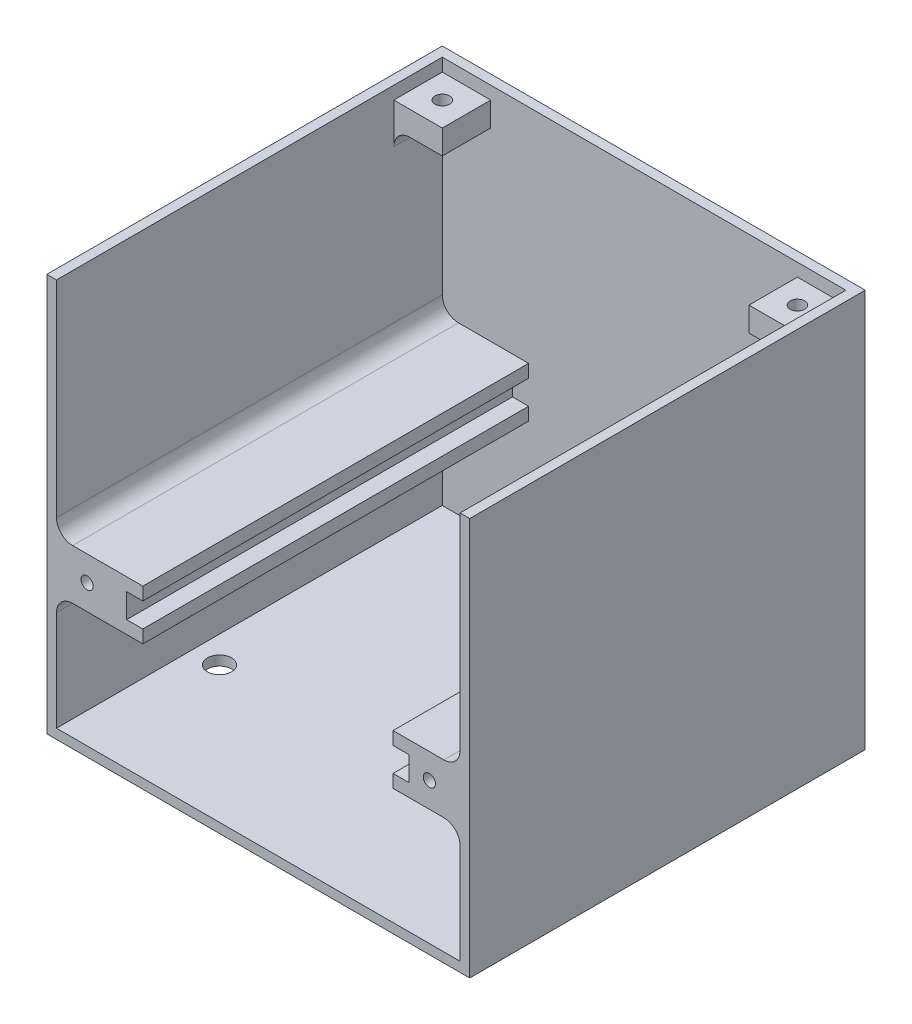
SolidWorks part; units mm, degrees
ref_plane "Front Plane" through (0, 0, 0) normal (0, 0, 1) x (1, 0, 0)
ref_plane "Top Plane" through (0, 0, 0) normal (0, 1, 0) x (1, 0, 0)
ref_plane "Right Plane" through (0, 0, 0) normal (1, 0, 0) x (0, 0, -1)
sketch "Sketch1" plane through (0, 0, 0) normal (0, 0, 1) x (1, 0, 0)
  line L0 (25, 1.2) -> (25, 49.3) construction
  line L1 (-26.2, 0) -> (26.2, 0)
  line L2 (-26.2, 0) -> (-26.2, 49.3)
  line L3 (-26.2, 49.3) -> (-25, 49.3) construction
  line L4 (26.2, 0) -> (26.2, 49.3)
  line L5 (-25, 1.2) -> (25, 1.2) construction
  line L6 (-25, 1.2) -> (-25, 49.3) construction
  line L7 (25, 49.3) -> (26.2, 49.3) construction
  line L8 (26.2, 49.3) -> (-26.2, 49.3)
  point P4 (0, 0)
  dimension "D1" = 52.4
  dimension "D2" = 49.3
  dimension "D3" = 1.2
extrude "Boss-Extrude1" add sketch "Sketch1" along normal blind 49
sketch "Sketch2" plane through (0, 0, 49) normal (0, 0, 1) x (1, 0, 0)
  line L0 (25, 1.2) -> (25, 49.3) construction
  line L1 (-25, 1.2) -> (25, 1.2) construction
  line L2 (-25, 1.2) -> (-25, 49.3) construction
  line L3 (26.2, 49.3) -> (-26.2, 49.3) construction
  line L4 (25, 1.2) -> (25, 15.6)
  line L5 (-25, 1.2) -> (25, 1.2)
  line L6 (-25, 1.2) -> (-25, 15.6)
  line L7 (25, 49.3) -> (-25, 49.3)
  line L8 (-25, 21.8) -> (-25, 49.3)
  line L9 (-16.3, 17.2) -> (-16.3, 20.2)
  line L10 (-25, 15.6) -> (-14.3, 15.6)
  line L11 (-16.3, 17.2) -> (-14.3, 17.2)
  line L12 (-16.3, 20.2) -> (-14.3, 20.2)
  line L13 (-14.3, 15.6) -> (-14.3, 17.2)
  line L14 (16.7, 15.6) -> (16.7, 17.2)
  line L15 (-25, 21.8) -> (-14.3, 21.8)
  line L16 (-14.3, 20.2) -> (-14.3, 21.8)
  line L17 (16.7, 20.2) -> (16.7, 21.8)
  line L18 (-14.3, 1.2) -> (-14.3, 60) construction
  line L19 (16.7, 21.8) -> (25, 21.8)
  line L20 (25, 21.8) -> (25, 49.3)
  line L21 (16.7, 20.2) -> (18.7, 20.2)
  line L22 (-25, 21.8) -> (25, 21.8) construction
  line L23 (16.7, 17.2) -> (18.7, 17.2)
  line L24 (-25, 20.2) -> (25, 20.2) construction
  line L25 (16.7, 15.6) -> (25, 15.6)
  line L26 (-25, 17.2) -> (25, 17.2) construction
  line L28 (-25, 15.6) -> (25, 15.6) construction
  line L29 (-16.3, 1.2) -> (-16.3, 60) construction
  line L30 (18.7, 17.2) -> (18.7, 20.2)
  point P3 (18.8, 1.2)
  point P4 (18.8, 60)
  point P21 (16.6, 1.2)
  point P22 (16.6, 60)
  dimension "D3" = 14.4
  dimension "D1" = 6.3
  dimension "D2" = 35
  dimension "D7" = 2
  dimension "D4" = 1.6
  dimension "D5" = 3
  dimension "D6" = 2
  dimension "D8" = 1.6
extrude "Cut-Extrude1" cut sketch "Sketch2" against normal offset from surface (47.8 mm away) 1.2 up to face at (0, 24.65, 0)
sketch "Sketch3" plane through (0, 0, 1.2) normal (0, 0, 1) x (1, 0, 0)
  line L0 (-25, 44.7) -> (-25, 47.7)
  line L1 (-25, 1.2) -> (-25, 49.3) construction
  line L2 (-25, 47.7) -> (-19, 47.7)
  line L3 (-19, 47.7) -> (-19, 44.7)
  line L4 (-19, 44.7) -> (-25, 44.7)
  line L5 (25, 47.7) -> (19, 47.7)
  line L6 (25, 1.2) -> (25, 49.3) construction
  line L7 (19, 47.7) -> (19, 44.7)
  line L8 (19, 44.7) -> (25, 44.7)
  line L9 (25, 44.7) -> (25, 47.7)
  line L10 (26.2, 49.3) -> (-26.2, 49.3) construction
  dimension "D1" = 6
  dimension "D2" = 6
  dimension "D3" = 1.6
  dimension "D4" = 3
extrude "Boss-Extrude2" add sketch "Sketch3" along normal blind 6
sketch "Sketch4" plane through (0, 0, 49) normal (0, 0, 1) x (1, 0, 0)
  line L0 (-16.3, 17.2) -> (-16.3, 20.2) construction
  line L2 (26.2, 0) -> (26.2, 49.3) construction
  line L3 (-26.2, 0) -> (-26.2, 49.3) construction
  circle A0 centre (-21.2, 18.7) radius 0.75
  circle A1 centre (21.2, 18.7) radius 0.75
  point P6 (-16.3, 18.7)
  dimension "D1" = 1.5
  dimension "D2" = 5
  dimension "D3" = 5
extrude "Cut-Extrude2" cut sketch "Sketch4" against normal blind 10
sketch "Sketch5" plane through (0, 1.2, 0) normal (0, 1, 0) x (1, 0, 0)
  line L0 (-25, -1.2) -> (-25, -49) construction
  line L1 (-25, -49) -> (25, -49) construction
  line L2 (25, -1.2) -> (25, -49) construction
  circle A0 centre (-21.7, -32.1) radius 1.5
  circle A1 centre (21.3, -27.6) radius 1.5
  dimension "D1" = 3
  dimension "D2" = 3.3
  dimension "D3" = 16.9
  dimension "D4" = 3.7
  dimension "D5" = 21.4
extrude "Cut-Extrude3" cut sketch "Sketch5" against normal through all
sketch "Sketch6" plane through (0, 47.7, 0) normal (0, 1, 0) x (1, 0, 0)
  line L0 (-25, -7.2) -> (-19, -1.2) construction
  line L1 (25, -7.2) -> (19, -1.2) construction
  circle A0 centre (22, -4.2) radius 0.9
  circle A1 centre (-22, -4.2) radius 0.9
  dimension "D1" = 1.8
extrude "Cut-Extrude4" cut sketch "Sketch6" against normal blind 5
fillet "Fillet1" radius 2 6 edges at (25, 15.6, 25.1) (-25, 15.6, 25.1) (-25, 21.8, 25.1) (25, 21.8, 25.1) (25, 44.7, 4.2) (-25, 44.7, 4.2)
